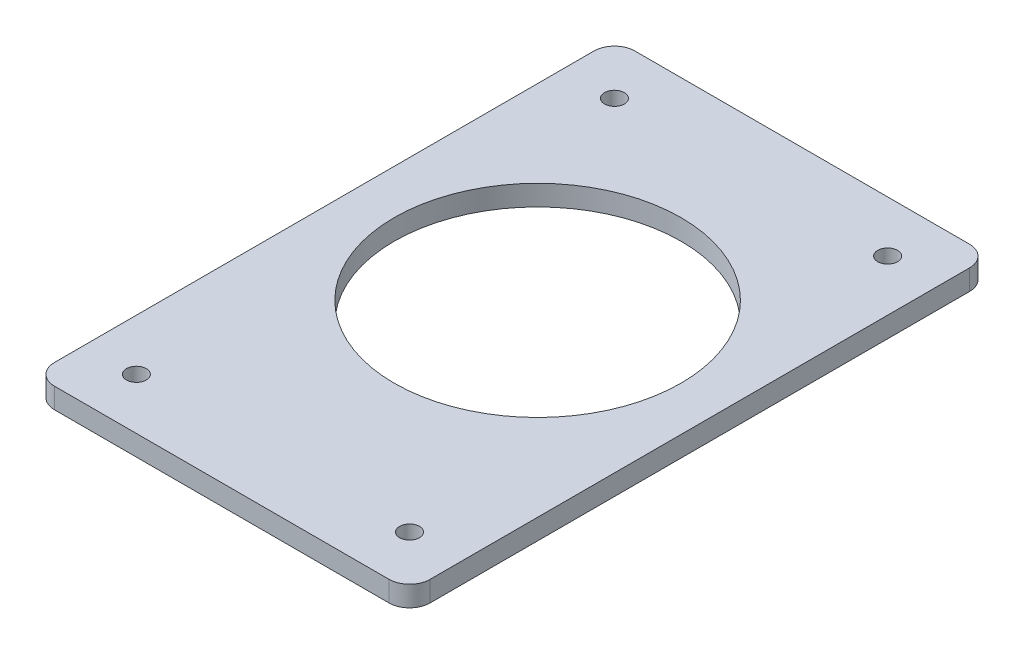
SolidWorks part; units mm, degrees
material "Thornel Mat VMA"
ref_plane "前视基准面" through (0, 0, 0) normal (0, 0, 1) x (1, 0, 0)
ref_plane "上视基准面" through (0, 0, 0) normal (0, 1, 0) x (1, 0, 0)
ref_plane "右视基准面" through (0, 0, 0) normal (1, 0, 0) x (0, 0, -1)
other "Configuration Table"
sketch "草图1" plane through (0, 0, 0) normal (0, 1, 0) x (1, 0, 0)
  line L0 (0, 0) -> (0, -3.75) construction
  line L1 (-27.5, -46.25) -> (27.5, -46.25)
  line L2 (-27.5, -46.25) -> (-27.5, 38.75)
  line L3 (-27.5, 38.75) -> (27.5, 38.75)
  line L4 (27.5, -46.25) -> (27.5, 38.75)
  line L5 (-27.5, -46.25) -> (27.5, 38.75) construction
  line L6 (-27.5, 38.75) -> (27.5, -46.25) construction
  circle A0 centre (0, 0) radius 21
  point P0 (-0.5267, -2.9359)
  dimension "D3" = 42
  dimension "D1" = 38.75
  dimension "D2" = 55
  dimension "D4" = 46.25
extrude "凸台-拉伸1" add sketch "草图1" along normal blind 3
sketch "草图2" plane through (0, 3, 0) normal (0, 1, 0) x (1, 0, 0)
  line L0 (-27.5, 31.25) -> (27.5, 31.25) construction
  line L1 (-27.5, 38.75) -> (-27.5, -46.25) construction
  line L2 (27.5, -46.25) -> (27.5, 38.75) construction
  line L3 (-27.5, -38.75) -> (27.5, -38.75) construction
  line L4 (0, 0) -> (0, 38.75) construction
  line L5 (27.5, 38.75) -> (-27.5, 38.75) construction
  line L6 (-27.5, -46.25) -> (27.5, -46.25) construction
  line L7 (20, -38.75) -> (20, 31.25) construction
  line L8 (-20, 31.25) -> (-20, -38.75) construction
  circle A0 centre (-20, 31.25) radius 1.45
  circle A1 centre (20, 31.25) radius 1.45
  circle A2 centre (-20, -38.75) radius 1.45
  circle A3 centre (20, -38.75) radius 1.45
  dimension "D1" = 2.9
  dimension "D2" = 2.9
  dimension "D3" = 20
  dimension "D6" = 7.5
  dimension "D7" = 2.9
  dimension "D8" = 2.9
  dimension "D4" = 20
  dimension "D5" = 7.5
extrude "切除-拉伸1" cut sketch "草图2" against normal blind 3
fillet "圆角1" radius 3 4 edges at (27.5, 1.5, 46.25) (-27.5, 1.5, 46.25) (27.5, 1.5, -38.75) (-27.5, 1.5, -38.75)
